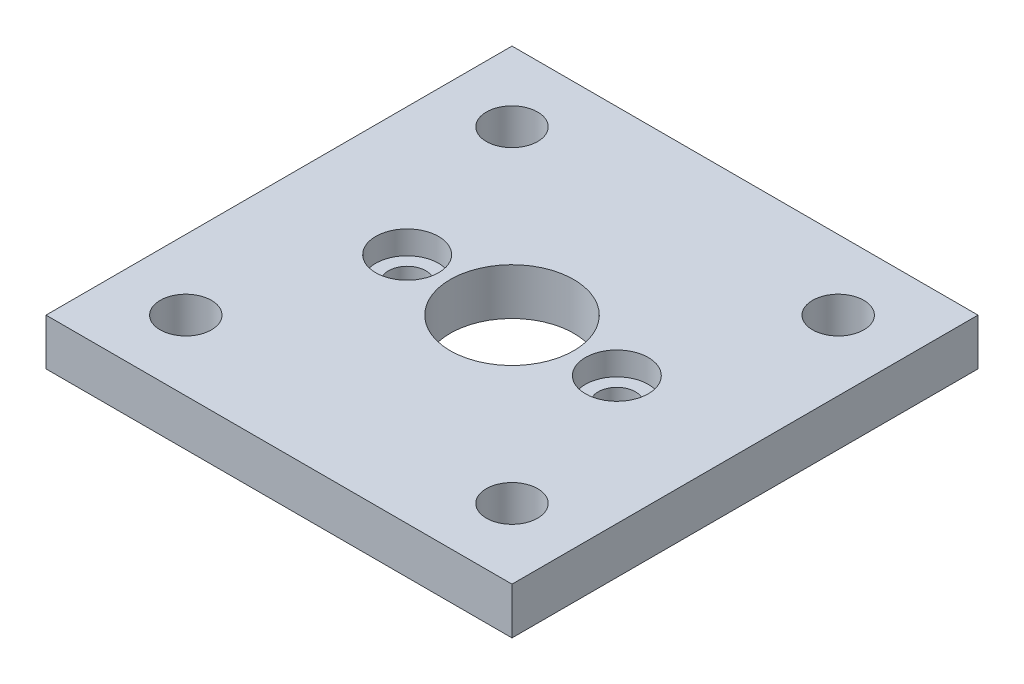
SolidWorks part; units mm, degrees
ref_plane "前视基准面" through (0, 0, 0) normal (0, 0, 1) x (1, 0, 0)
ref_plane "上视基准面" through (0, 0, 0) normal (0, 1, 0) x (1, 0, 0)
ref_plane "右视基准面" through (0, 0, 0) normal (1, 0, 0) x (0, 0, -1)
other "Configuration Table"
sketch "草图1" plane through (0, 0, 0) normal (0, 1, 0) x (1, 0, 0)
  line L0 (-4.5, 0) -> (4.5, 0) construction
  line L22 (-10, -10) -> (10, -10)
  line L23 (-10, -10) -> (-10, 10)
  line L28 (-10, 10) -> (10, 10)
  line L29 (10, -10) -> (10, 10)
  line L37 (-10, -10) -> (10, 10) construction
  line L38 (-10, 10) -> (10, -10) construction
  circle A5 centre (-4.5, 0) radius 0.8
  circle A6 centre (4.5, 0) radius 0.8
  circle A7 centre (0, 0) radius 2.65
  point P0 (0, 0)
  dimension "D3" = 1.6
  dimension "D4" = 5.3
  dimension "D1" = 9
  dimension "D2" = 20
extrude "凸台-拉伸1" add sketch "草图1" along normal blind 2
sketch "草图2" plane through (0, 2, 0) normal (0, 1, 0) x (1, 0, 0)
  circle A0 centre (-4.5, 0) radius 1.35
  circle A1 centre (4.5, 0) radius 1.35
  dimension "D1" = 2.7
extrude "切除-拉伸1" cut sketch "草图2" against normal blind 1
sketch "草图3" plane through (0, 0, 0) normal (0, -1, 0) x (1, 0, 0)
  line L1 (-10, -10) -> (-10, 10) construction
  line L2 (-10, 10) -> (10, 10) construction
  line L3 (10, -10) -> (-10, -10) construction
  line L4 (10, 10) -> (10, -10) construction
  circle A4 centre (-7, 7) radius 1.1
  circle A5 centre (7, 7) radius 1.1
  circle A6 centre (7, -7) radius 1.1
  circle A7 centre (-7, -7) radius 1.1
  point P18 (0, 0)
  dimension "D1" = 2.2
  dimension "D3" = 3
  dimension "D4" = 3
  dimension "D5" = 3
  dimension "D6" = 3
extrude "切除-拉伸2" cut sketch "草图3" against normal through all
